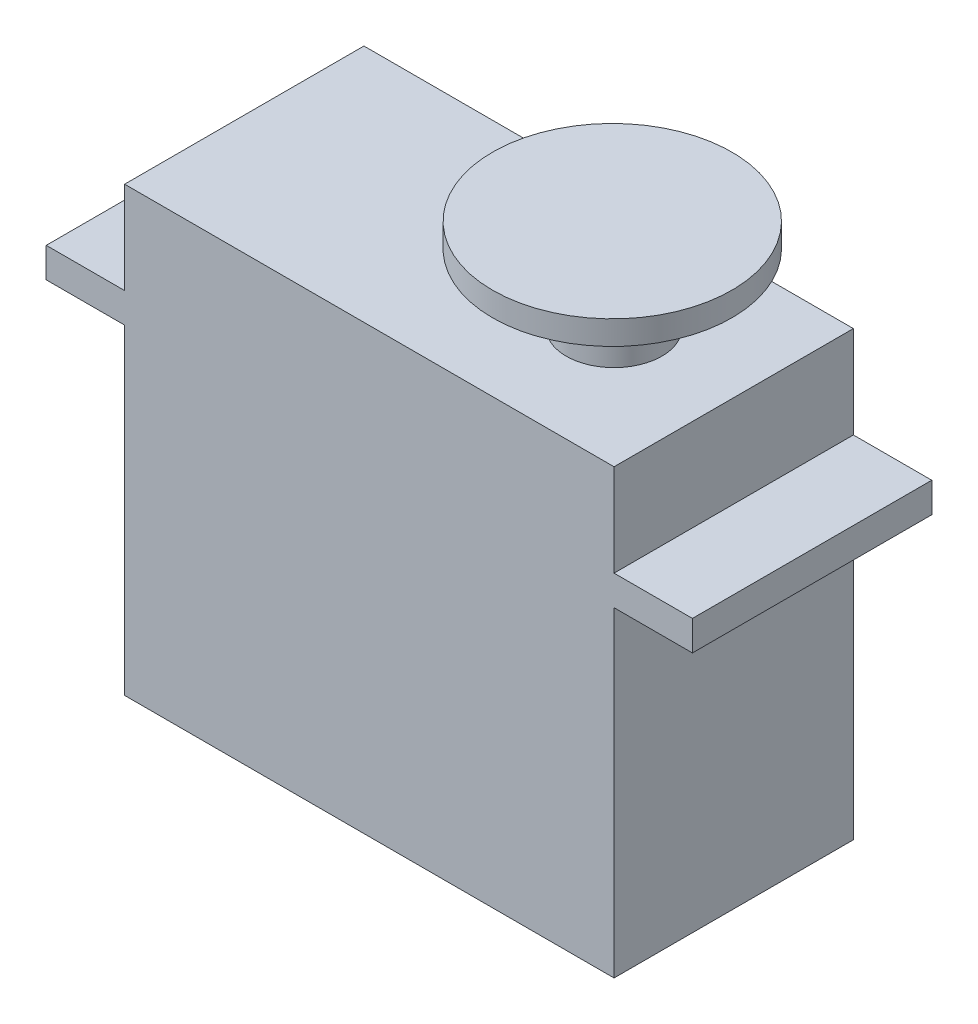
SolidWorks part; units mm, degrees
ref_plane "Front Plane" through (0, 0, 0) normal (0, 0, 1) x (1, 0, 0)
ref_plane "Top Plane" through (0, 0, 0) normal (0, 1, 0) x (1, 0, 0)
ref_plane "Right Plane" through (0, 0, 0) normal (1, 0, 0) x (0, 0, -1)
other "Center of Mass"
sketch "Sketch2" plane through (0, 0, 0) normal (0, 1, 0) x (1, 0, 0)
  line L1 (-27, -10) -> (27, -10)
  line L2 (-27, -10) -> (-27, 10)
  line L3 (-27, 10) -> (27, 10)
  line L4 (27, -10) -> (27, 10)
  line L5 (-27, -10) -> (27, 10) construction
  line L6 (-27, 10) -> (27, -10) construction
  point P0 (0, 0)
  dimension "D1" = 20
  dimension "D2" = 54
extrude "Boss-Extrude1" add sketch "Sketch2" along normal blind 2.5
sketch "Sketch4" plane through (0, 0, 0) normal (0, -1, 0) x (1, 0, 0)
  line L0 (-27, 10) -> (27, 10) construction
  line L1 (-20.45, -10) -> (20.45, -10)
  line L2 (-20.45, -10) -> (-20.45, 10)
  line L3 (-20.45, 10) -> (20.45, 10)
  line L4 (20.45, -10) -> (20.45, 10)
  line L5 (-20.45, -10) -> (20.45, 10) construction
  line L6 (-20.45, 10) -> (20.45, -10) construction
  point P0 (0, 0)
  dimension "D1" = 40.9
extrude "Boss-Extrude2" add sketch "Sketch4" along normal blind 26.8
sketch "Sketch5" plane through (0, 2.5, 0) normal (0, 1, 0) x (1, 0, 0)
  line L0 (27, 10) -> (-27, 10) construction
  line L1 (-20.45, -10) -> (20.45, -10)
  line L2 (-20.45, -10) -> (-20.45, 10)
  line L3 (-20.45, 10) -> (20.45, 10)
  line L4 (20.45, -10) -> (20.45, 10)
  line L5 (-20.45, -10) -> (20.45, 10) construction
  line L6 (-20.45, 10) -> (20.45, -10) construction
  point P0 (0, 0)
  dimension "D1" = 40.9
extrude "Boss-Extrude3" add sketch "Sketch5" along normal blind 7.7
sketch "Sketch6" plane through (0, 10.2, 0) normal (0, 1, 0) x (1, 0, 0)
  line L0 (-20.45, 0) -> (21.8064, 0) construction
  line L1 (-20.45, 10) -> (-20.45, -10) construction
  line L2 (20.45, -10) -> (20.45, 10) construction
  circle A0 centre (10.45, 0) radius 4
  dimension "D1" = 8
  dimension "D2" = 10
extrude "Boss-Extrude4" add sketch "Sketch6" along normal blind 5.7
sketch "Sketch7" plane through (0, 15.9, 0) normal (0, 1, 0) x (1, 0, 0)
  circle A0 centre (10.3011, 0) radius 10
extrude "Boss-Extrude5" add sketch "Sketch7" along normal blind 2
